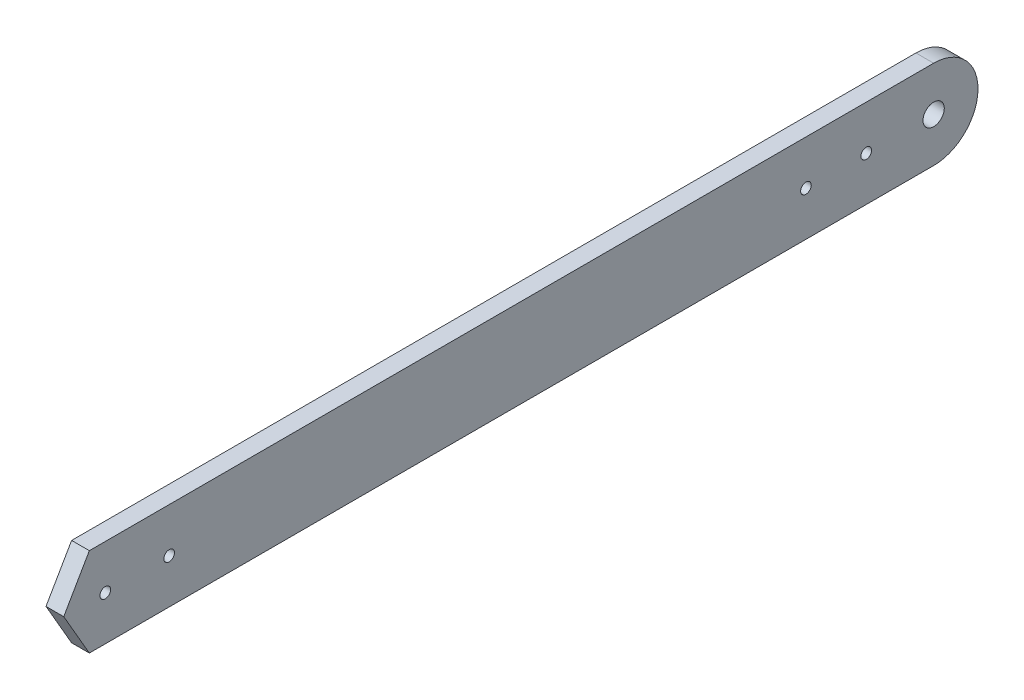
SolidWorks part; units mm, degrees
ref_plane "Front Plane" through (0, 0, 0) normal (0, 0, 1) x (1, 0, 0)
ref_plane "Top Plane" through (0, 0, 0) normal (0, 1, 0) x (1, 0, 0)
ref_plane "Right Plane" through (0, 0, 0) normal (1, 0, 0) x (0, 0, -1)
sketch "Sketch1" plane through (0, 0, 0) normal (0, 0, 1) x (1, 0, 0)
  line L1 (-2.5, -12.5) -> (2.5, -12.5)
  line L2 (-2.5, -12.5) -> (-2.5, 12.5)
  line L3 (-2.5, 12.5) -> (2.5, 12.5)
  line L4 (2.5, -12.5) -> (2.5, 12.5)
  line L5 (-2.5, -12.5) -> (2.5, 12.5) construction
  line L6 (-2.5, 12.5) -> (2.5, -12.5) construction
  point P0 (0, 0)
  dimension "D2" = 5
  dimension "D3" = 25
extrude "Boss-Extrude1" add sketch "Sketch1" along normal blind 258.5
sketch "Sketch2" plane through (2.5, 0, 0) normal (1, 0, 0) x (0, 0, -1)
  line L0 (-258.5, 0) -> (0, 0) construction
  line L1 (-258.5, -12.5) -> (-258.5, 12.5) construction
  line L2 (0, -12.5) -> (0, 12.5) construction
  line L3 (-12.5, 12.5) -> (5.5, 12.5)
  line L4 (5.5, 12.5) -> (5.5, -12.5)
  line L5 (5.5, -12.5) -> (-12.5, -12.5)
  line L9 (-257.7169, 0) -> (-250.5, 12.5)
  line L10 (-258.5, 12.5) -> (0, 12.5) construction
  line L11 (-250.5, 12.5) -> (-258.5, 12.5)
  line L12 (-258.5, 12.5) -> (-258.5, -12.5)
  line L13 (-258.5, -12.5) -> (-250.5, -12.5)
  line L14 (-258.5, -12.5) -> (0, -12.5) construction
  line L15 (-250.5, -12.5) -> (-257.7169, 0)
  circle A0 centre (-12.5, 0) radius 3
  circle A1 centre (-246, 0) radius 1.5
  circle A2 centre (-228, 0) radius 1.5
  arc A3 (-12.5, -12.5) -> (-12.5, 12.5) centre (-12.5, 0) ccw
  circle A5 centre (-48.5, 0) radius 1.5
  circle A6 centre (-31.5, 0) radius 1.5
  point P23 (-136.7058, 0)
  dimension "D1" = 6
  dimension "D2" = 12.5
  dimension "D4" = 3
  dimension "D5" = 18
  dimension "D7" = 120
  dimension "D8" = 19
  dimension "D9" = 17
  dimension "D3" = 12.5
  dimension "D6" = 18
  dimension "D10" = 4.5
extrude "Cut-Extrude1" cut sketch "Sketch2" against normal through all
